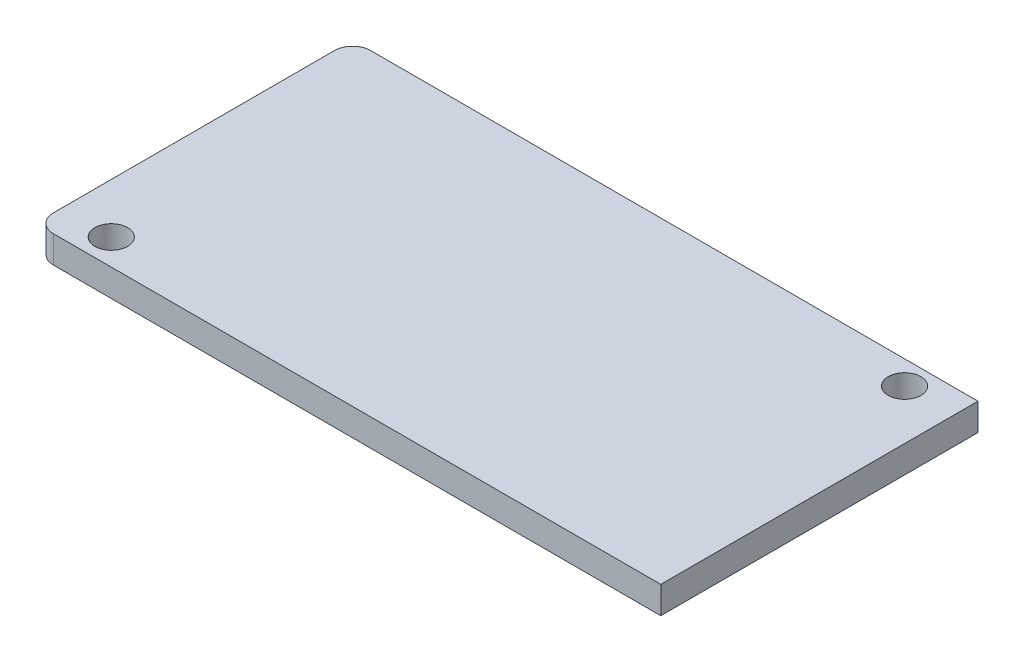
SolidWorks part; units mm, degrees
ref_plane "Front Plane" through (0, 0, 0) normal (0, 0, 1) x (1, 0, 0)
ref_plane "Top Plane" through (0, 0, 0) normal (0, 1, 0) x (1, 0, 0)
ref_plane "Right Plane" through (0, 0, 0) normal (1, 0, 0) x (0, 0, -1)
sketch "Sketch1" plane through (0, 0, 0) normal (0, 1, 0) x (1, 0, 0)
  line L1 (-34.5, 17.5) -> (34.5, 17.5)
  line L2 (-34.5, 17.5) -> (-34.5, -17.5)
  line L3 (-34.5, -17.5) -> (34.5, -17.5)
  line L4 (34.5, 17.5) -> (34.5, -17.5)
  line L5 (-34.5, 17.5) -> (34.5, -17.5) construction
  line L6 (-34.5, -17.5) -> (34.5, 17.5) construction
  point P0 (0, 0)
  dimension "D1" = 69
  dimension "D2" = 35
extrude "Boss-Extrude1" add sketch "Sketch1" along normal blind 3
fillet "Fillet4" radius 2 2 edges at (-34.5, 1.5, 17.5) (-34.5, 1.5, -17.5)
sketch "Sketch2" plane through (0, 0, 0) normal (0, -1, 0) x (1, 0, 0)
  circle A0 centre (-29, 14.625) radius 1.8
  circle A1 centre (29, -14.8983) radius 1.8
extrude "Cut-Extrude1" cut sketch "Sketch2" against normal up to next
